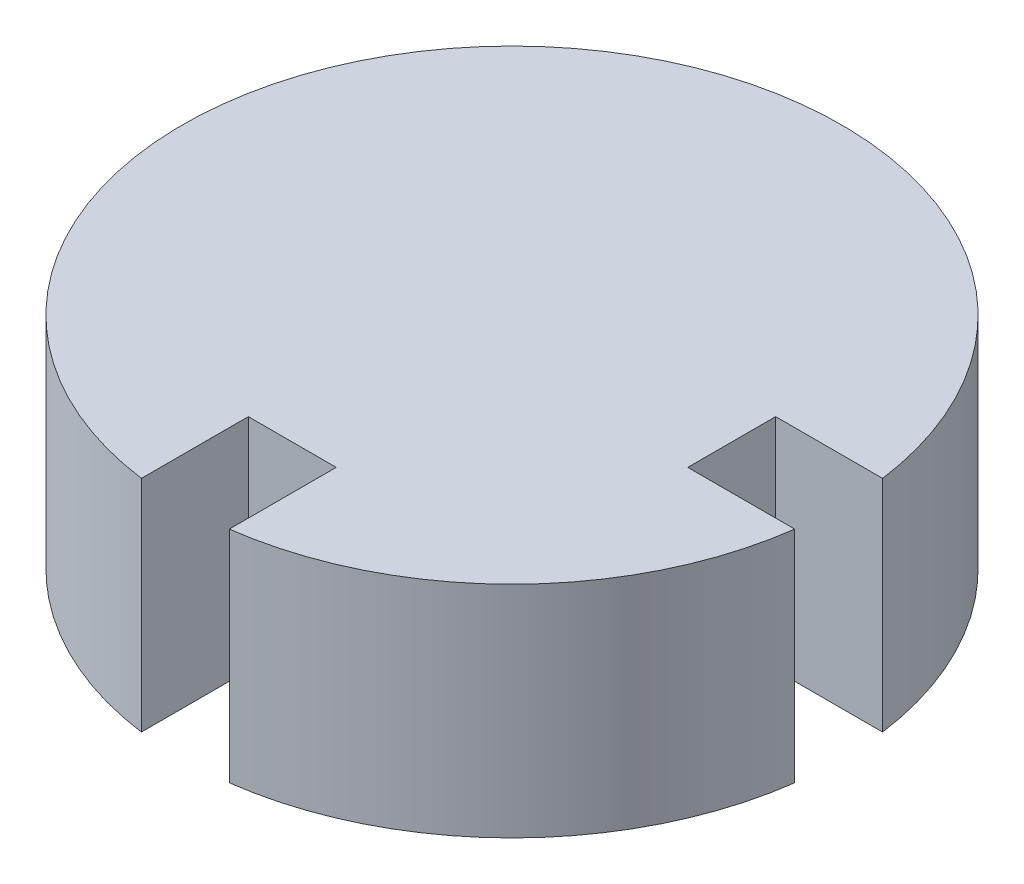
SolidWorks part; units mm, degrees
ref_plane "Front Plane" through (0, 0, 0) normal (0, 0, 1) x (1, 0, 0)
ref_plane "Top Plane" through (0, 0, 0) normal (0, 1, 0) x (1, 0, 0)
ref_plane "Right Plane" through (0, 0, 0) normal (1, 0, 0) x (0, 0, -1)
sketch "Sketch2" plane through (0, 0, 0) normal (0, 1, 0) x (1, 0, 0)
  line L3 (-0.4, -4) -> (0.4, -4)
  line L4 (-0.4, -4) -> (-0.4, -2)
  line L5 (-0.4, -2) -> (0.4, -2)
  line L6 (0.4, -4) -> (0.4, -2)
  line L7 (-0.4, -4) -> (0.4, -2) construction
  line L8 (-0.4, -2) -> (0.4, -4) construction
  line L10 (4, -0.4) -> (2, -0.4)
  line L11 (4, -0.4) -> (4, 0.4)
  line L12 (4, 0.4) -> (2, 0.4)
  line L13 (2, -0.4) -> (2, 0.4)
  line L14 (4, -0.4) -> (2, 0.4) construction
  line L15 (4, 0.4) -> (2, -0.4) construction
  circle A2 centre (0, 0) radius 3
  point P3 (0, -3)
  point P9 (3, 0)
  dimension "D3" = 0.8
  dimension "D4" = 1
  dimension "D1" = 2
  dimension "D2" = 0.8
  dimension "D5" = 1
extrude "Boss-Extrude1" add sketch "Sketch2" along normal blind 2 contours L6 A2 L10 L13 L12 L4 L5
